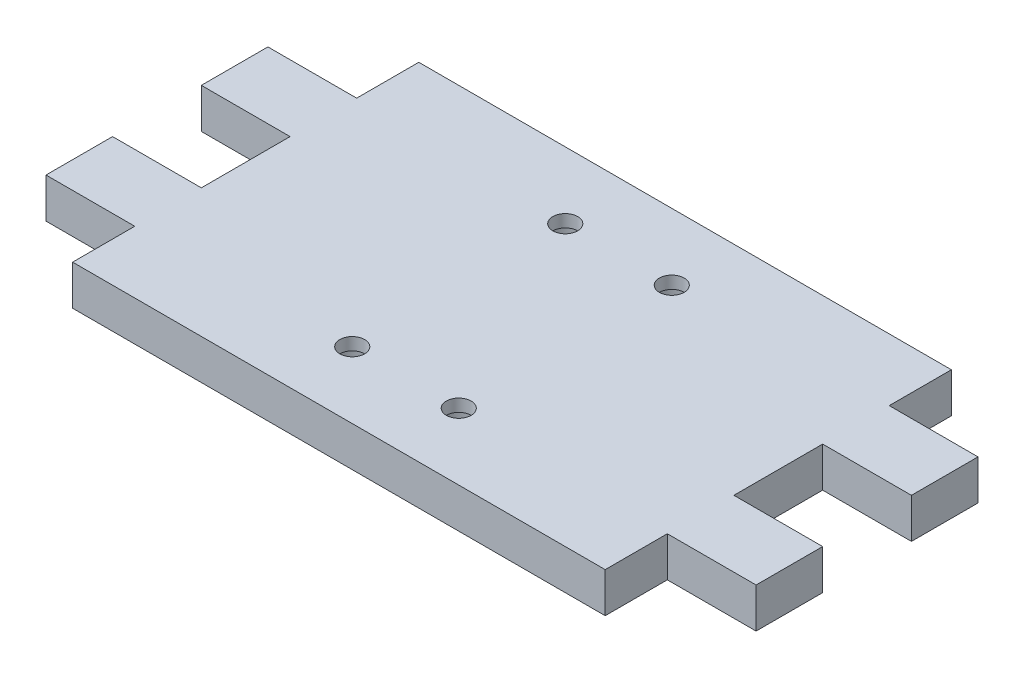
SolidWorks part; units mm, degrees
ref_plane "Front Plane" through (0, 0, 0) normal (0, 0, 1) x (1, 0, 0)
ref_plane "Top Plane" through (0, 0, 0) normal (0, 1, 0) x (1, 0, 0)
ref_plane "Right Plane" through (0, 0, 0) normal (1, 0, 0) x (0, 0, -1)
sketch "Sketch1" plane through (0, 0, 0) normal (1, 0, 0) x (0, 0, -1)
  line L1 (-12.5, -2.25) -> (12.5, -2.25)
  line L2 (-12.5, -2.25) -> (-12.5, 2.25)
  line L3 (-12.5, 2.25) -> (12.5, 2.25)
  line L4 (12.5, -2.25) -> (12.5, 2.25)
  line L5 (-12.5, -2.25) -> (12.5, 2.25) construction
  line L6 (-12.5, 2.25) -> (12.5, -2.25) construction
  point P0 (0, 0)
  dimension "D1" = 4.5
  dimension "D2" = 25
extrude "Boss-Extrude1" add sketch "Sketch1" along normal mid plane 60
sketch "Sketch2" plane through (30, 0, 0) normal (1, 0, 0) x (0, 0, -1)
  line L5 (12.5, 2.25) -> (-12.5, 2.25) construction
  line L6 (-12.5, 2.25) -> (-5, 2.25)
  line L7 (-12.5, 2.25) -> (-12.5, -2.25)
  line L8 (-12.5, -2.25) -> (-5, -2.25)
  line L9 (-5, 2.25) -> (-5, -2.25)
  line L10 (5, 2.25) -> (12.5, 2.25)
  line L11 (5, 2.25) -> (5, -2.25)
  line L12 (5, -2.25) -> (12.5, -2.25)
  line L13 (12.5, 2.25) -> (12.5, -2.25)
  line L14 (-12.5, -2.25) -> (12.5, -2.25) construction
  line L15 (-12.5, 2.25) -> (-12.5, -2.25) construction
  line L16 (12.5, -2.25) -> (12.5, 2.25) construction
  dimension "D1" = 7.5
  dimension "D2" = 7.5
extrude "Boss-Extrude2" add sketch "Sketch2" along normal blind 10
sketch "Esquisse1" plane through (0, 0, 12.5) normal (0, 0, 1) x (1, 0, 0)
  line L0 (40, -2.25) -> (-30, -2.25) construction
  line L1 (-30, 2.25) -> (30, 2.25)
  line L2 (-30, 2.25) -> (-30, -2.25)
  line L3 (-30, -2.25) -> (30, -2.25)
  line L4 (30, 2.25) -> (30, -2.25)
  dimension "D1" = 60
extrude "Boss.-Extru.1" add sketch "Esquisse1" along normal blind 7
mirror "Symétrie1" about plane through (0, 0, 0) normal (0, 0, 1) of "Boss.-Extru.1"
mirror "Mirror1" about plane through (0, 0, 0) normal (1, 0, 0) of "Boss-Extrude2"
hole_wizard "CBORE for M3 SBHCS2" positions "Sketch4" profile "Sketch5" counterbore size "M3" standard "ANSI Metric" end condition through all
sketch "Sketch4" plane through (0, -2.25, 0) normal (0, -1, 0) x (-1, 0, 0)
  line L0 (-6, 12) -> (-6, -12) construction
  line L1 (-6, -12) -> (6, -12) construction
  line L2 (6, -12) -> (6, 12) construction
  line L3 (6, 12) -> (-6, 12) construction
  point P0 (-6, 12)
  point P3 (6, 12)
  point P6 (6, -12)
  point P9 (-6, -12)
  point P18 (6, 0)
  point P20 (0, 12)
  dimension "D1" = 12
  dimension "D2" = 24
sketch "Sketch5" plane through (6, -2.25, -12) normal (1, 0, 0) x (0, 0, -1)
  line L0 (0, 0) -> (0, 4.5)
  line L1 (0, 4.5) -> (1.4, 4.5)
  line L3 (1.4, 4.5) -> (1.4, 3.1)
  line L4 (1.4, 3.1) -> (2.75, 3.1)
  line L5 (2.75, 3.1) -> (2.75, 0)
  line L7 (2.75, 0) -> (0, 0)
  line L11 (0, -6.35) -> (0, 107.95) construction
  dimension "Thru Hole Dia." = 2.8
  dimension "Thru Hole Depth" = 4.5
  dimension "C'Bore Dia." = 5.5
  dimension "C'Bore Depth" = 3.1
